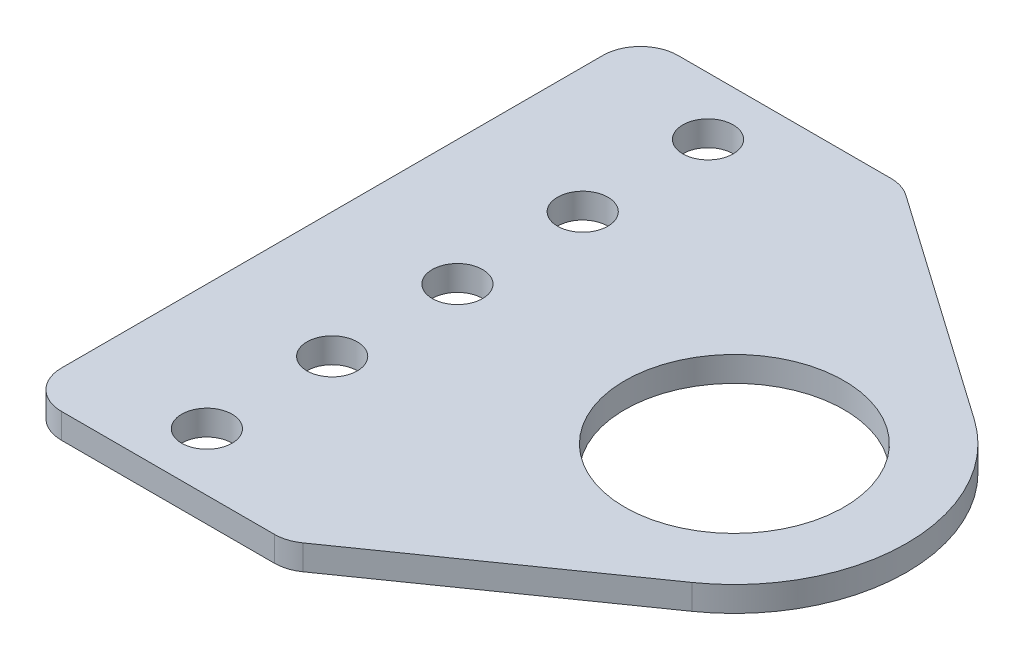
SolidWorks part; units mm, degrees
material "5052-H32"
ref_plane "Front Plane" through (0, 0, 0) normal (0, 0, 1) x (1, 0, 0)
ref_plane "Top Plane" through (0, 0, 0) normal (0, 1, 0) x (1, 0, 0)
ref_plane "Right Plane" through (0, 0, 0) normal (1, 0, 0) x (0, 0, -1)
sketch "Sketch1" plane through (0, 0, 0) normal (0, 1, 0) x (1, 0, 0)
  line L0 (-40.775, -27.44) -> (-40.775, 27.44)
  line L1 (-15.375, -31.25) -> (-36.965, -31.25)
  line L2 (-36.965, 31.25) -> (-15.375, 31.25)
  line L3 (-13.189, -30.5605) -> (10.0193, -14.3022)
  line L4 (10.0193, 14.3022) -> (-13.189, 30.5605)
  line L5 (-15.375, 31.25) -> (-15.375, -31.25) construction
  circle A0 centre (0, 0) radius 11.1125
  circle A1 centre (-28.075, 25.4) radius 2.5527
  circle A2 centre (-28.075, 12.7) radius 2.5527
  circle A3 centre (-28.075, 0) radius 2.5527
  circle A4 centre (-28.075, -12.7) radius 2.5527
  circle A5 centre (-28.075, -25.4) radius 2.5527
  arc A7 (10.0193, -14.3022) -> (10.0193, 14.3022) centre (0, 0) ccw
  arc A9 (-36.965, 31.25) -> (-40.775, 27.44) centre (-36.965, 27.44) ccw
  arc A10 (-40.775, -27.44) -> (-36.965, -31.25) centre (-36.965, -27.44) ccw
  arc A13 (-15.375, -31.25) -> (-13.189, -30.5605) centre (-15.375, -27.44) ccw
  arc A14 (-15.375, 31.25) -> (-13.189, 30.5605) centre (-15.375, 27.44) cw
  point P12 (-14.1732, -31.25)
  point P23 (-14.1732, 31.25)
  dimension "D1" = 5.1054
  dimension "D2" = 22.225
  dimension "D3" = 17.4625
  dimension "D4" = 3.81
  dimension "D9" = 3.81
  dimension "D10" = 12.7
  dimension "D11" = 12.7
  dimension "D12" = 12.7
  dimension "D5" = 12.7
  dimension "D6" = 31.25
  dimension "D7" = 31.25
  dimension "D8" = 40.775
  dimension "D13" = 12.7
  dimension "D14" = 25.4
extrude "Boss-Extrude1" add sketch "Sketch1" along normal blind 2.54
